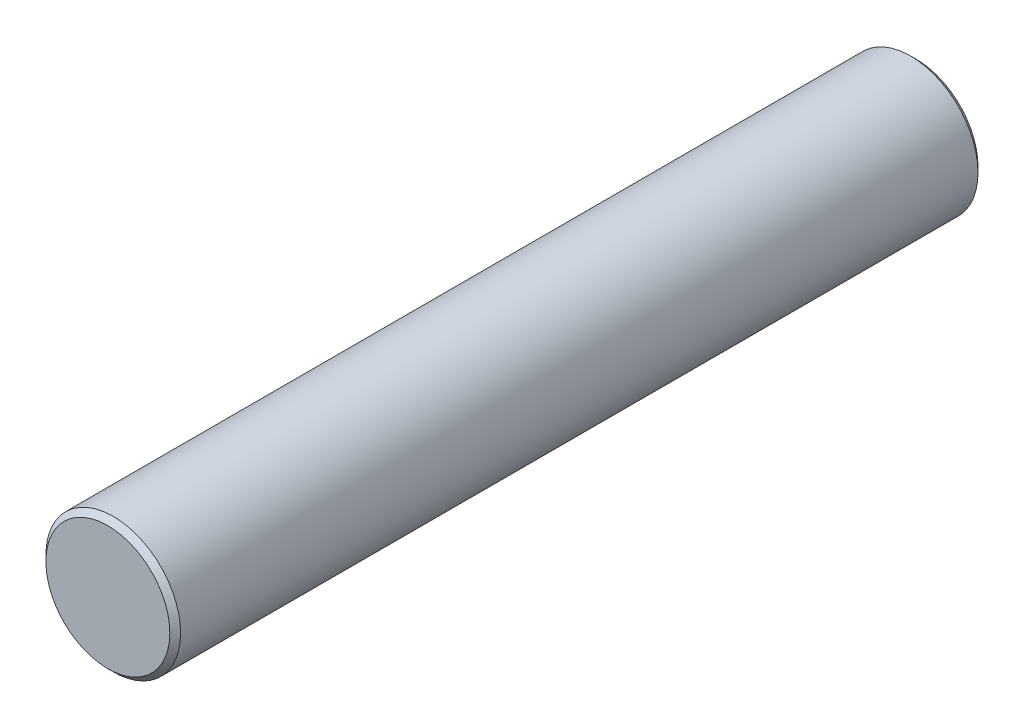
SolidWorks part; units mm, degrees
ref_plane "Front Plane" through (0, 0, 0) normal (0, 0, 1) x (1, 0, 0)
ref_plane "Top Plane" through (0, 0, 0) normal (0, 1, 0) x (1, 0, 0)
ref_plane "Right Plane" through (0, 0, 0) normal (1, 0, 0) x (0, 0, -1)
sketch "Sketch1" plane through (0, 0, 0) normal (0, 0, 1) x (1, 0, 0)
  circle A0 centre (0, 0) radius 2.5
  dimension "D1" = 5
extrude "Boss-Extrude1" add sketch "Sketch1" against normal blind 30
chamfer "Chamfer1" distance 0.2 angle 45 2 edges at (2.5, 0, -30) (2.5, 0, 0)
ref_plane "Plane1" through (0, 0, -15) normal (0, 0, 1) x (1, 0, 0)
